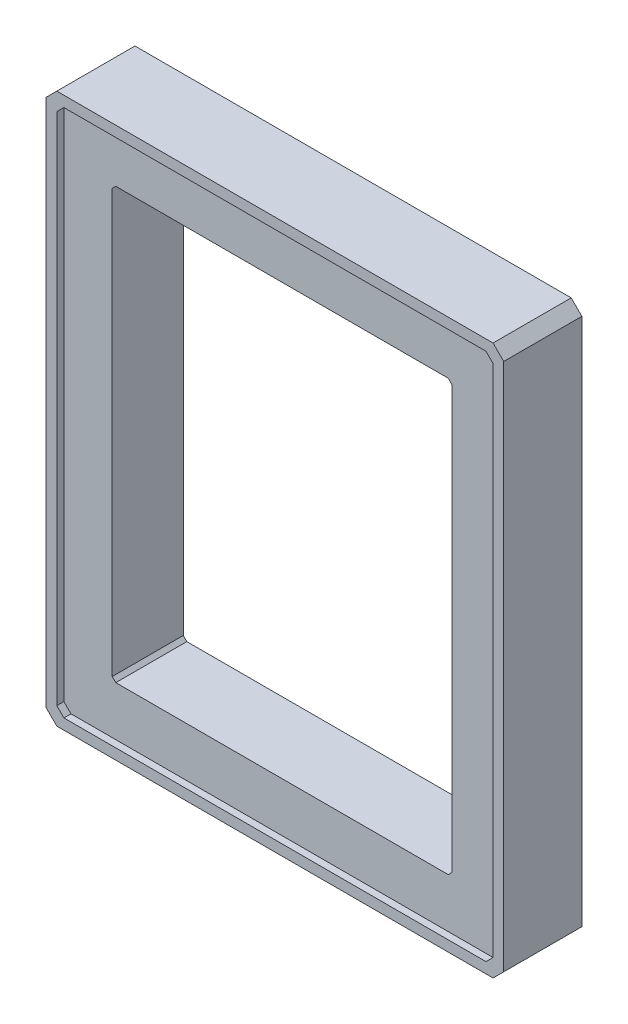
SolidWorks part; units mm, degrees
ref_plane "前视基准面" through (0, 0, 0) normal (0, 0, 1) x (1, 0, 0)
ref_plane "上视基准面" through (0, 0, 0) normal (0, 1, 0) x (1, 0, 0)
ref_plane "右视基准面" through (0, 0, 0) normal (1, 0, 0) x (0, 0, -1)
other "Configuration Table"
sketch "草图1" plane through (0, 0, 0) normal (0, 0, 1) x (1, 0, 0)
  line L0 (-61.4, -77.4) -> (61.4, -77.4)
  line L1 (61.4, -77.4) -> (64.4, -74.4)
  line L2 (64.4, -74.4) -> (64.4, 74.4)
  line L3 (64.4, 74.4) -> (61.4, 77.4)
  line L4 (61.4, 77.4) -> (-61.4, 77.4)
  line L5 (-61.4, 77.4) -> (-64.4, 74.4)
  line L6 (-64.4, 74.4) -> (-64.4, -74.4)
  line L7 (-64.4, -74.4) -> (-61.4, -77.4)
  line L8 (-46.8, -60.5) -> (46.8, -60.5)
  line L9 (46.8, -60.5) -> (47.8, -59.5)
  line L10 (47.8, -59.5) -> (47.8, 59.5)
  line L11 (47.8, 59.5) -> (46.8, 60.5)
  line L12 (46.8, 60.5) -> (-46.8, 60.5)
  line L13 (-46.8, 60.5) -> (-47.8, 59.5)
  line L14 (-47.8, 59.5) -> (-47.8, -59.5)
  line L15 (-47.8, -59.5) -> (-46.8, -60.5)
  dimension "D1" = 46.8
  dimension "D2" = 47.8
  dimension "D3" = 61.4
  dimension "D4" = 64.4
  dimension "D5" = 46.8
  dimension "D6" = 61.4
  dimension "D7" = 59.5
  dimension "D8" = 60.5
  dimension "D9" = 74.4
  dimension "D10" = 77.4
  dimension "D11" = 59.5
  dimension "D12" = 74.4
extrude "Support_plane_exactly_20mm_above_table" add sketch "草图1" along normal blind 20
sketch "草图2" plane through (0, 0, 0) normal (0, 0, 1) x (1, 0, 0)
  line L0 (-61.4, -77.4) -> (61.4, -77.4)
  line L1 (61.4, -77.4) -> (64.4, -74.4)
  line L2 (64.4, -74.4) -> (64.4, 74.4)
  line L3 (64.4, 74.4) -> (61.4, 77.4)
  line L4 (61.4, 77.4) -> (-61.4, 77.4)
  line L5 (-61.4, 77.4) -> (-64.4, 74.4)
  line L6 (-64.4, 74.4) -> (-64.4, -74.4)
  line L7 (-64.4, -74.4) -> (-61.4, -77.4)
  line L8 (-59.4, -74.4) -> (59.4, -74.4)
  line L9 (59.4, -74.4) -> (61.4, -72.4)
  line L10 (61.4, -72.4) -> (61.4, 72.4)
  line L11 (61.4, 72.4) -> (59.4, 74.4)
  line L12 (59.4, 74.4) -> (-59.4, 74.4)
  line L13 (-59.4, 74.4) -> (-61.4, 72.4)
  line L14 (-61.4, 72.4) -> (-61.4, -72.4)
  line L15 (-61.4, -72.4) -> (-59.4, -74.4)
  dimension "D1" = 59.4
  dimension "D2" = 61.4
  dimension "D3" = 64.4
  dimension "D4" = 59.4
  dimension "D5" = 72.4
  dimension "D6" = 74.4
  dimension "D7" = 77.4
  dimension "D8" = 72.4
extrude "Low_locating_lip_0p4mm_clearance_each_side" add sketch "草图2" along normal blind 2 from offset 20
